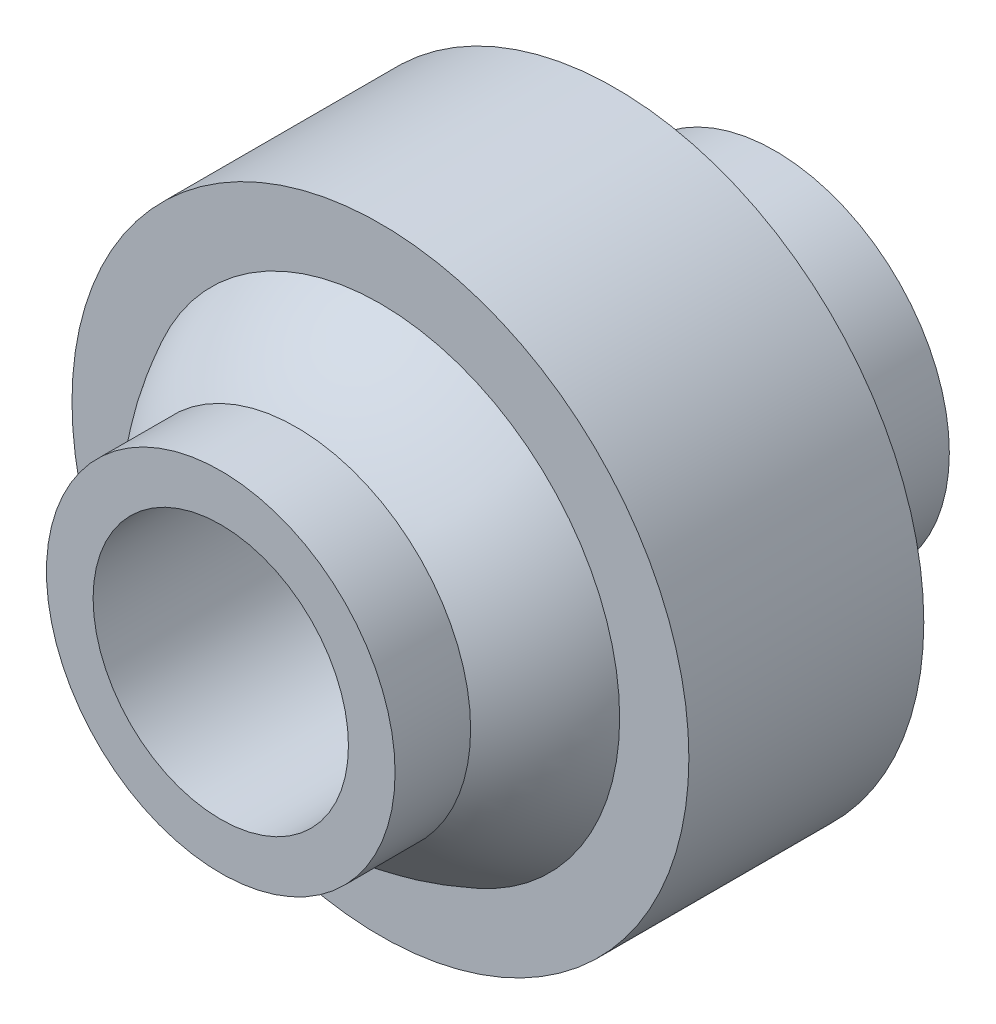
SolidWorks part; units mm, degrees
material "Alloy Steel"
ref_plane "X-Y Datum" through (0, 0, 0) normal (0, 0, 1) x (1, 0, 0)
ref_plane "X-Z Datum" through (0, 0, 0) normal (0, 1, 0) x (1, 0, 0)
ref_plane "Y-Z Datum" through (0, 0, 0) normal (1, 0, 0) x (0, 0, -1)
sketch "Sketch1" plane through (0, 0, 0) normal (1, 0, 0) x (0, 0, -1)
  line L0 (82.1362, -22.0492) -> (50082.1362, -22.0492) construction
  line L1 (71.12, -5.2479) -> (71.12, 49994.7521) construction
  line L2 (66.7385, -30.973) -> (71.12, -22.0492) construction
  line L3 (71.12, -22.0492) -> (63.6, -28.5516) construction
  line L4 (60.7822, -26.8117) -> (81.4578, -26.8117)
  line L5 (60.7822, -28.5516) -> (63.6, -28.5516)
  line L6 (66.7385, -30.973) -> (66.7385, -33.5554)
  line L7 (66.7385, -33.5554) -> (75.5015, -33.5554)
  line L8 (75.5015, -33.5554) -> (75.5015, -30.973)
  line L11 (78.64, -28.5516) -> (81.4578, -28.5516)
  line L28 (81.4578, -28.5516) -> (81.4578, -26.8117) construction
  line L39 (60.7822, -26.8117) -> (60.7822, -28.5516)
  line L40 (81.4578, -26.8117) -> (81.4578, -28.5516)
  arc A0 (63.6, -28.5516) -> (66.7385, -30.973) centre (71.12, -22.0492) ccw
  arc A1 (75.5015, -30.973) -> (78.64, -28.5516) centre (71.12, -22.0492) ccw
  point P8 (71.12, -26.8117)
  point P15 (71.12, -33.5554)
  dimension "D1" = 9.525
  dimension "D3" = 8.763
  dimension "D5" = 23
  dimension "D2" = 13.0048
  dimension "D4" = 20.6756
  dimension "D6" = 23.0124
revolve "Revolve1" add sketch "Sketch1" angle 360 about L0
